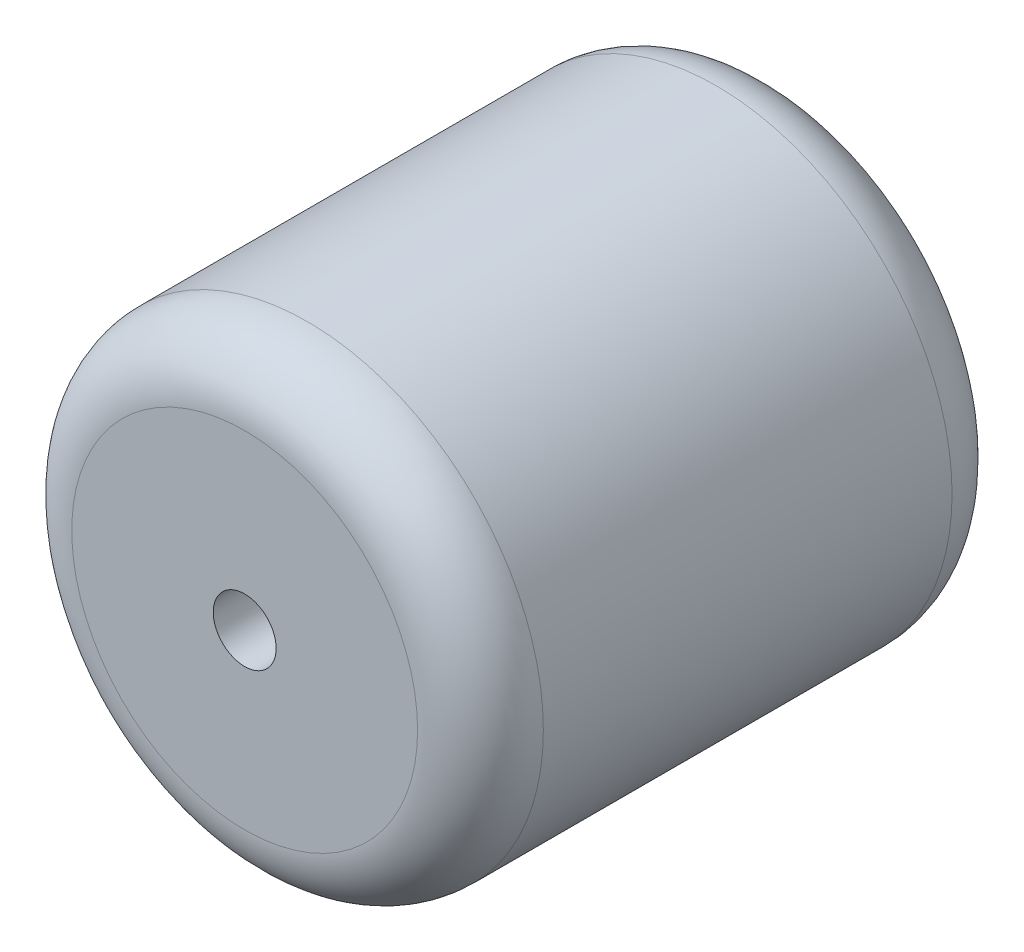
SolidWorks part; units mm, degrees
ref_plane "Front Plane" through (0, 0, 0) normal (0, 0, 1) x (1, 0, 0)
ref_plane "Top Plane" through (0, 0, 0) normal (0, 1, 0) x (1, 0, 0)
ref_plane "Right Plane" through (0, 0, 0) normal (1, 0, 0) x (0, 0, -1)
sketch "Sketch3" plane through (0, 0, 0) normal (0, 0, 1) x (1, 0, 0)
  circle A0 centre (0, 0) radius 7.5
  point P3 (-155.1621, -53.6067)
extrude "Boss-Extrude2" add sketch "Sketch3" along normal blind 17 contours A0
sketch "Sketch5" plane through (0, 0, 17) normal (0, 0, 1) x (1, 0, 0)
  circle A0 centre (0, 0) radius 1
extrude "Cut-Extrude1" cut sketch "Sketch5" against normal blind 17
fillet "Fillet5" radius 2 1 edges at (7.5, 0, 17)
fillet "Fillet6" radius 2 1 edges at (7.5, 0, 0)
